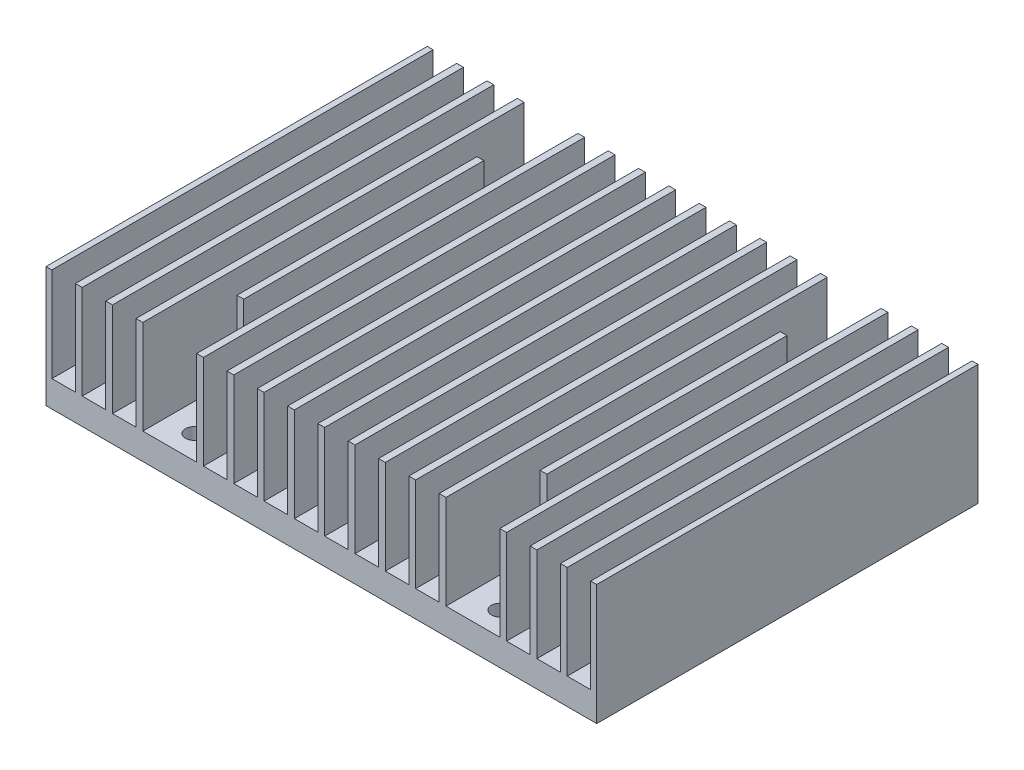
SolidWorks part; units mm, degrees
ref_plane "Front Plane" through (0, 0, 0) normal (0, 0, 1) x (1, 0, 0)
ref_plane "Top Plane" through (0, 0, 0) normal (0, 1, 0) x (1, 0, 0)
ref_plane "Right Plane" through (0, 0, 0) normal (1, 0, 0) x (0, 0, -1)
sketch "Sketch1" plane through (0, 0, 0) normal (0, 1, 0) x (1, 0, 0)
  line L1 (0, 0) -> (148.59, 0)
  line L2 (0, 0) -> (0, 102.87)
  line L3 (0, 102.87) -> (148.59, 102.87)
  line L4 (148.59, 0) -> (148.59, 102.87)
  dimension "D1" = 102.87
  dimension "D2" = 148.59
extrude "Extrude1" add sketch "Sketch1" along normal blind 32.512
sketch "Sketch2" plane through (0, 32.512, 0) normal (0, 1, 0) x (-1, 0, 0)
  line L0 (-148.59, -102.87) -> (0, -102.87) construction
  line L1 (-1.5875, -102.87) -> (-7.9375, -102.87)
  line L2 (-1.5875, -102.87) -> (-1.5875, 0)
  line L3 (-1.5875, 0) -> (-7.9375, 0)
  line L4 (-7.9375, -102.87) -> (-7.9375, 0)
  line L5 (0, 0) -> (-148.59, 0) construction
  line L6 (0, -102.87) -> (0, 0) construction
  dimension "D1" = 6.35
  dimension "D2" = 1.5875
extrude "Cut-Extrude1" cut sketch "Sketch2" against normal blind 25.4
pattern_linear "LPattern1" count 18 spacing 8.1788 along (1, 0, 0) of "Cut-Extrude1"
sketch "Sketch3" plane through (0, 0, 0) normal (0, -1, 0) x (1, 0, 0)
  line L0 (0, -102.87) -> (0, 0) construction
  line L2 (148.59, -102.87) -> (0, -102.87) construction
  circle A0 centre (33.5788, -6.35) radius 2.286
  circle A1 centre (33.5788, -94.742) radius 2.286
  circle A2 centre (116.1288, -6.35) radius 2.286
  circle A3 centre (116.1288, -94.742) radius 2.286
  dimension "D1" = 4.572
  dimension "D3" = 88.392
  dimension "D6" = 88.392
  dimension "D7" = 82.55
  dimension "D2" = 33.5788
  dimension "D4" = 8.128
extrude "Cut-Extrude2" cut sketch "Sketch3" against normal blind 78.74
sketch "Sketch4" plane through (0, 32.512, 0) normal (0, 1, 0) x (-1, 0, 0)
  line L1 (-34.3027, -92.5736) -> (-34.3027, -8.5184) construction
  line L2 (-32.4739, -102.87) -> (-34.3027, -102.87)
  line L3 (-32.4739, -102.87) -> (-32.4739, -83.82)
  line L4 (-32.4739, -83.82) -> (-34.3027, -83.82)
  line L6 (-34.3027, -102.87) -> (-34.3027, -83.82)
  line L7 (-116.0907, -92.4563) -> (-116.0907, -8.6357) construction
  line L8 (-114.2619, -102.87) -> (-116.0907, -102.87)
  line L9 (-114.2619, -102.87) -> (-114.2619, -83.82)
  line L11 (-114.2619, -83.82) -> (-116.0907, -83.82)
  line L12 (-116.0907, -102.87) -> (-116.0907, -83.82)
  line L13 (-32.4739, -8.3512) -> (-32.4739, -92.7408) construction
  line L14 (-34.3027, 0) -> (-32.4739, 0)
  line L16 (-34.3027, 0) -> (-34.3027, -19.05)
  line L17 (-34.3027, -19.05) -> (-32.4739, -19.05)
  line L18 (-32.4739, 0) -> (-32.4739, -19.05)
  line L20 (-114.2619, 0) -> (-116.0907, 0)
  line L21 (-114.2619, 0) -> (-114.2619, -19.05)
  line L22 (-114.2619, -19.05) -> (-116.0907, -19.05)
  line L23 (-116.0907, 0) -> (-116.0907, -19.05)
  dimension "D1" = 19.05
  dimension "D2" = 19.05
  dimension "D3" = 19.05
  dimension "D4" = 19.05
extrude "Cut-Extrude3" cut sketch "Sketch4" against normal blind 25.4
